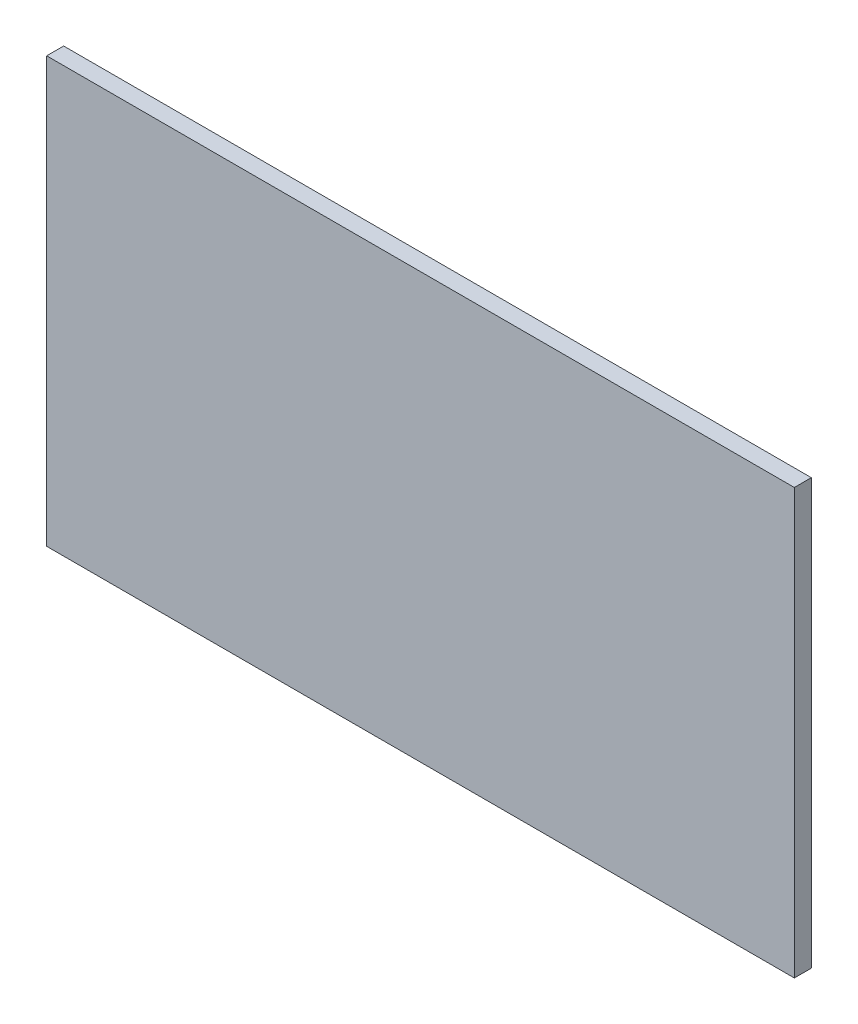
SolidWorks part; units mm, degrees
ref_plane "Front Plane" through (0, 0, 0) normal (0, 0, 1) x (1, 0, 0)
ref_plane "Top Plane" through (0, 0, 0) normal (0, 1, 0) x (1, 0, 0)
ref_plane "Right Plane" through (0, 0, 0) normal (1, 0, 0) x (0, 0, -1)
sketch "Sketch2" plane through (0, 0, 0) normal (0, 0, 1) x (1, 0, 0)
  line L1 (0, 0) -> (880, 0)
  line L2 (0, 0) -> (0, -500)
  line L3 (0, -500) -> (880, -500)
  line L4 (880, 0) -> (880, -500)
  dimension "D1" = 880
  dimension "D2" = 500
extrude "Boss-Extrude1" add sketch "Sketch2" along normal blind 20
